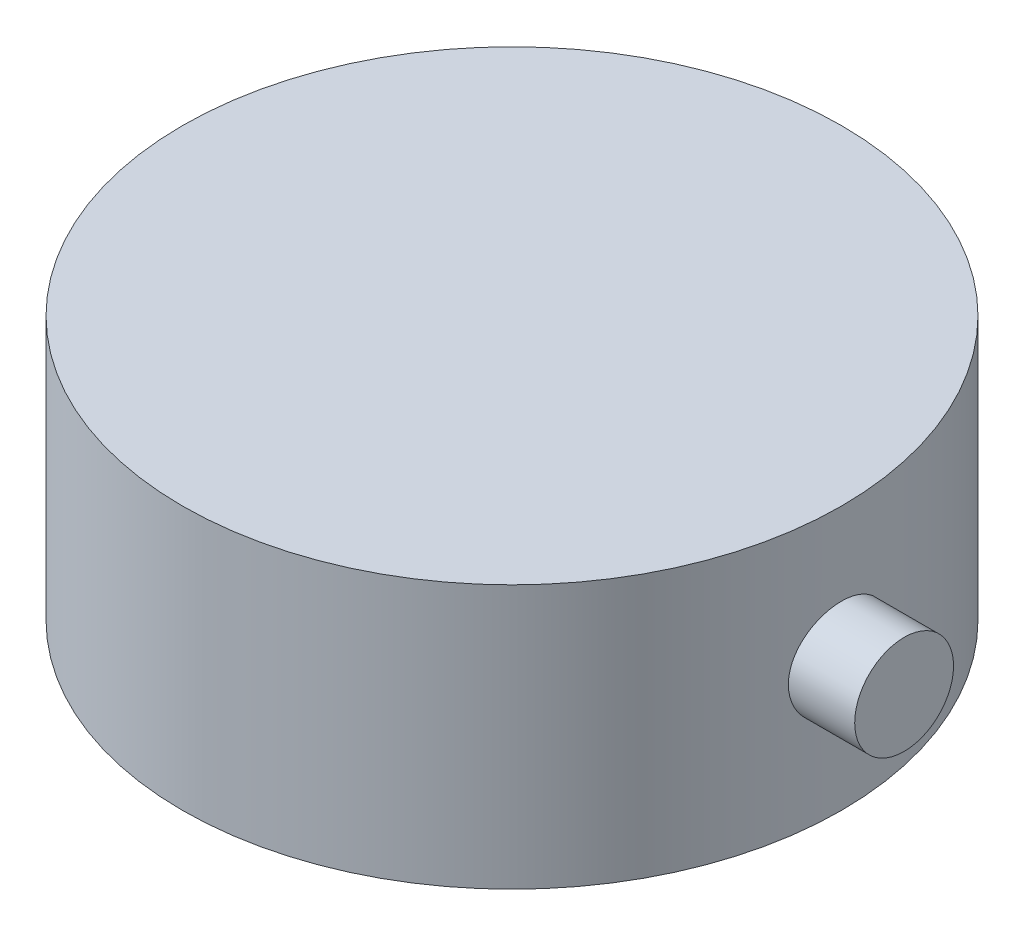
SolidWorks part; units mm, degrees
ref_plane "Ebene vorne" through (0, 0, 0) normal (1, 0, 0) x (0, 1, 0)
ref_plane "Ebene oben" through (0, 0, 0) normal (0, 0, 1) x (0, 1, 0)
ref_plane "Ebene rechts" through (0, 0, 0) normal (0, 1, 0) x (-1, 0, 0)
sketch "Skizze1" plane through (0, 0, 0) normal (0, 0, 1) x (0, 1, 0)
  circle A0 centre (0, 0) radius 50
  dimension "D1" = 100
extrude "Aufsatz-Linear austragen1" add sketch "Skizze1" along normal mid plane 40
sketch "Skizze2" plane through (0, 0, 20) normal (0, 0, 1) x (1, 0, 0)
  circle A2 centre (0, 0) radius 40
  circle A3 centre (0, 0) radius 40
  dimension "D1" = 10
extrude "Schnitt-Linear austragen1" cut sketch "Skizze2" against normal blind 5
sketch "Skizze3" plane through (0, 0, 0) normal (0, 1, 0) x (-1, 0, 0)
  line L0 (0, -20) -> (0, 20) construction
  line L1 (-50, -20) -> (50, -20) construction
  line L2 (40, 20) -> (-40, 20) construction
  circle A0 centre (0, 0) radius 7.5
  dimension "D1" = 15
extrude "Aufsatz-Linear austragen2" add sketch "Skizze3" along normal mid plane 119
sketch "Skizze4" [suppressed] plane through (0, 0, 0) normal (0, 0, 1) x (0, 1, 0)
  line L0 (59.5, -7.5) -> (59.5, 7.5) construction
  line L1 (-59.5, 10) -> (59.5, 10) construction
  line L2 (-59.5, 10) -> (-59.5, -70)
  line L3 (-59.5, -70) -> (59.5, -70)
  line L4 (59.5, 10) -> (59.5, -70)
  line L5 (-59.5, 7.5) -> (-59.5, -7.5) construction
  line L6 (69.5, 10) -> (69.5, -80)
  line L7 (-69.5, -80) -> (69.5, -80)
  line L8 (-69.5, 10) -> (-69.5, -80)
  line L9 (-69.5, 10) -> (-59.5, 10)
  line L10 (59.5, 10) -> (69.5, 10)
  dimension "D1" = 10
  dimension "D2" = 80
  dimension "D3" = 10
extrude "Aufsatz-Linear austragen3" [suppressed] add sketch "Skizze4" along normal mid plane 60
chamfer "Fase1" [suppressed] distance 10 angle 45
sketch "Skizze5" [suppressed] plane through (0, 0, 30) normal (0, 0, 1) x (1, 0, 0)
  line L1 (70, 59.5) -> (-130, 59.5)
  line L2 (70, 59.5) -> (70, -59.5)
  line L3 (70, -59.5) -> (-130, -59.5)
  line L4 (-130, 59.5) -> (-130, -59.5)
  dimension "D1" = 200
extrude "Schnitt-Linear austragen2" [suppressed] cut sketch "Skizze5" against normal through all both and the other way through all
scale "Skalieren1" scale about centroid uniform scaling yes scale factor 0.75
move or copy body "Körper-Verschieben/Kopieren1" bodies to move or copy 107 copy no rotation origin (0, 0, 0) rotation axis (0.5774, 0.5774, -0.5774) rotation angle 120
